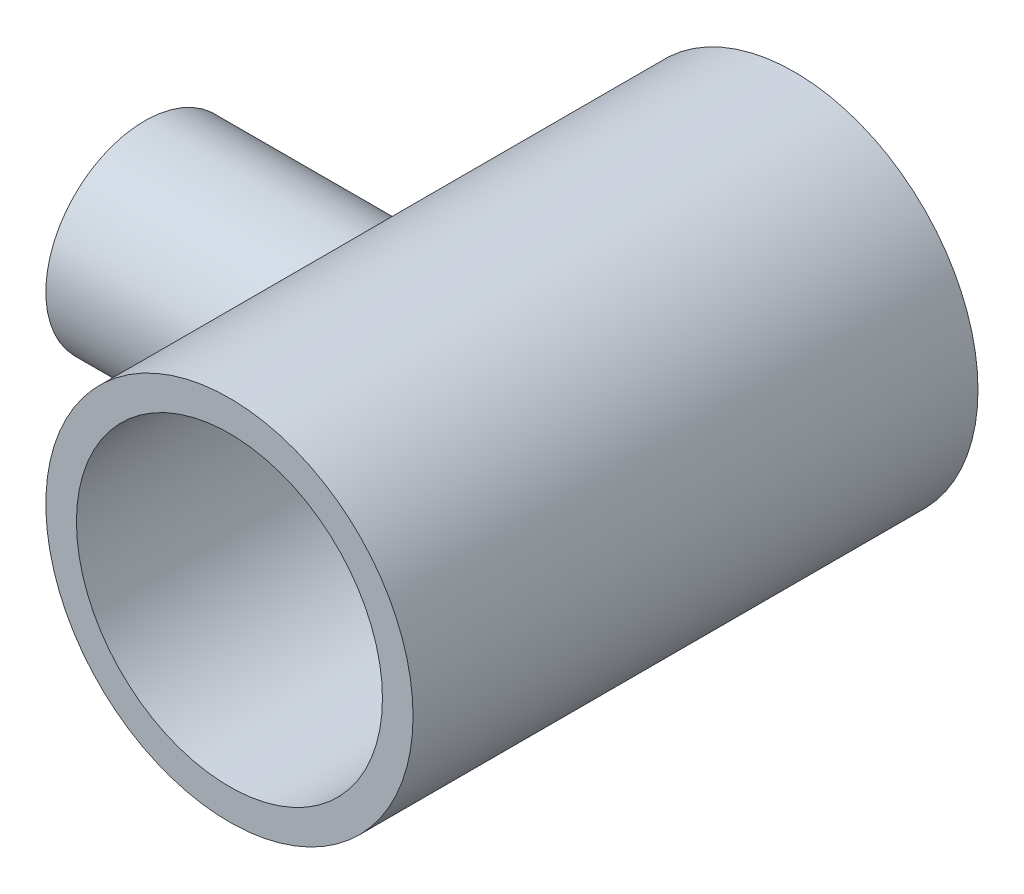
SolidWorks part; units mm, degrees
ref_plane "Front Plane" through (0, 0, 0) normal (0, 0, 1) x (1, 0, 0)
ref_plane "Top Plane" through (0, 0, 0) normal (0, 1, 0) x (1, 0, 0)
ref_plane "Right Plane" through (0, 0, 0) normal (1, 0, 0) x (0, 0, -1)
sketch "Sketch1" plane through (0, 0, 0) normal (0, 0, 1) x (1, 0, 0)
  line L0 (0, 0) -> (0, 12.1685) construction
  line L1 (-5.8532, 0) -> (9.704, 0) construction
  circle A0 centre (0, 0) radius 20.6375
  circle A1 centre (0, 0) radius 24.765
  dimension "D1" = 41.275
  dimension "D2" = 49.53
sketch3d "3DSketch1"
  line L0 (0, 0, 0) -> (0, 0, -76.2) construction
  dimension "D1" = 76.2
extrude "Boss-Extrude1" add sketch "Sketch1" along normal blind 76.2
sketch "Sketch2" plane through (0, 0, 0) normal (1, 0, 0) x (0, 0, -1)
  line L0 (0, 0) -> (-76.2, 0) construction
  line L1 (-76.2, 24.765) -> (-76.2, -24.765) construction
  circle A0 centre (-38.1, 0) radius 9.525
  dimension "D1" = 19.05
extrude "Cut-Extrude1" cut sketch "Sketch2" against normal blind 76.2
ref_plane "Plane1" through (-24.13, 0, 0) normal (1, 0, 0) x (0, 0, -1)
sketch "Sketch3" plane through (-24.13, 0, 0) normal (1, 0, 0) x (0, 0, -1)
  circle A0 centre (-38.1, 0) radius 9.525
  circle A1 centre (-38.1, 0) radius 9.525 construction
  circle A2 centre (-38.1, 0) radius 13.335
  dimension "D1" = 26.67
extrude "Boss-Extrude2" add sketch "Sketch3" against normal blind 25.4 contours A2 A0
sketch "Sketch4" plane through (-24.13, 0, 0) normal (1, 0, 0) x (0, 0, -1)
  circle A0 centre (-38.1, 0) radius 13.335
  circle A1 centre (-38.1, 0) radius 9.525
  circle A2 centre (-38.1, 0) radius 9.525 construction
  circle A3 centre (-38.1, 0) radius 13.335 construction
extrude "Boss-Extrude3" add sketch "Sketch4" along normal blind 3.4
